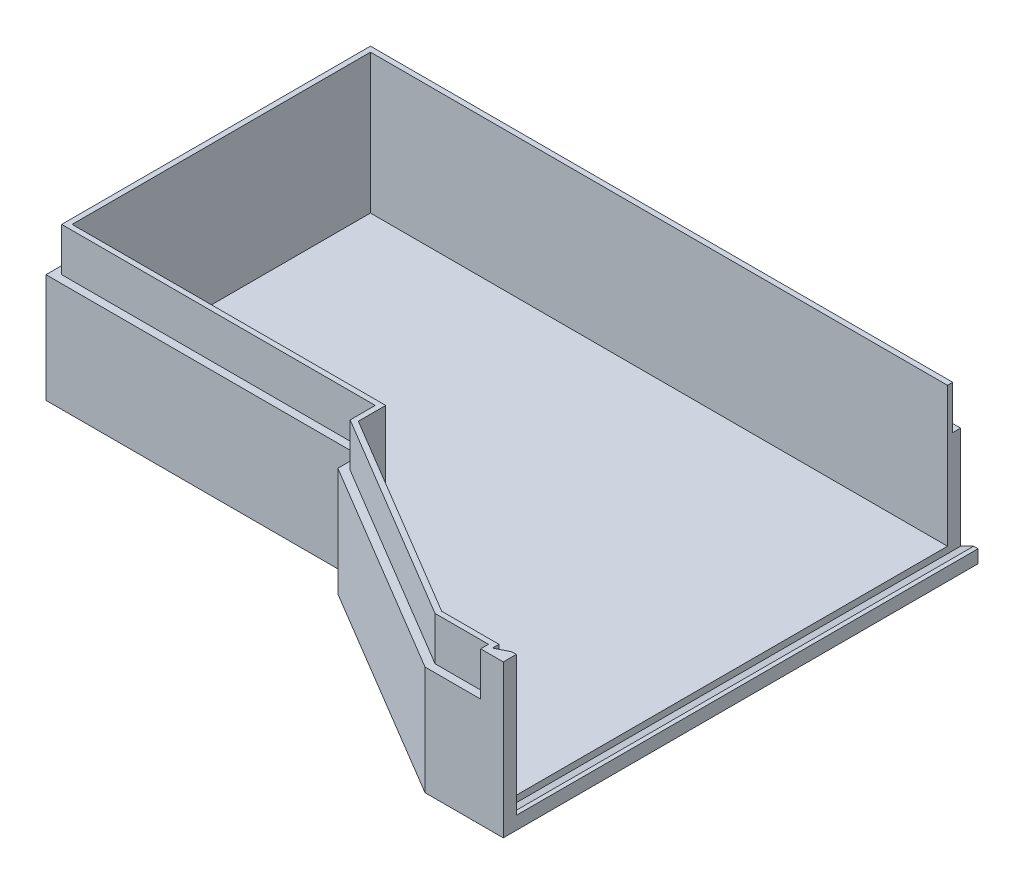
SolidWorks part; units mm, degrees
ref_plane "Front Plane" through (0, 0, 0) normal (0, 0, 1) x (1, 0, 0)
ref_plane "Top Plane" through (0, 0, 0) normal (0, 1, 0) x (1, 0, 0)
ref_plane "Right Plane" through (0, 0, 0) normal (1, 0, 0) x (0, 0, -1)
sketch "PCB" plane through (0, 0, 0) normal (0, 1, 0) x (1, 0, 0)
  line L0 (0, 0) -> (131.5, 0)
  line L1 (131.5, 0) -> (131.5, -102)
  line L2 (131.5, -102) -> (119, -102)
  line L3 (0, 0) -> (0, -67.5)
  line L4 (0, -67.5) -> (72, -67.5)
  line L5 (72, -67.5) -> (72, -74)
  line L6 (72, -74) -> (119, -102)
  line L7 (71.5, -74.2841) -> (118.8624, -102.5)
  line L8 (132, -102.5) -> (118.8624, -102.5)
  line L9 (132, 0.5) -> (132, -102.5)
  line L10 (-0.5, 0.5) -> (132, 0.5)
  line L11 (-0.5, 0.5) -> (-0.5, -68)
  line L12 (-0.5, -68) -> (71.5, -68)
  line L13 (71.5, -68) -> (71.5, -74.2841)
  line L14 (68.5, -75.9889) -> (118.0365, -105.5)
  line L15 (135, -105.5) -> (118.0365, -105.5)
  line L17 (-3.5, 3.5) -> (135, 3.5)
  line L18 (-3.5, 3.5) -> (-3.5, -71)
  line L19 (-3.5, -71) -> (68.5, -71)
  line L20 (68.5, -71) -> (68.5, -75.9889)
  line L22 (135, 3.5) -> (136, 3.5)
  line L24 (135, -105.5) -> (136, -105.5)
  line L25 (136, 3.5) -> (136, -105.5)
  line L26 (135, 3.5) -> (135, -105.5) construction
  dimension "D1" = 131.5
  dimension "D2" = 102
  dimension "D3" = 12.5
  dimension "D4" = 67.5
  dimension "D5" = 72
  dimension "D6" = 6.5
  dimension "D9" = 1
  dimension "D7" = 0.5
  dimension "D8" = 3
extrude "Boss-Extrude1" add sketch "PCB" along normal blind 35 contours L25 L24 L15 L14 L20 L19 L18 L17 L22
sketch "Sketch4" plane through (0, 35, 0) normal (0, 1, 0) x (1, 0, 0)
  line L14 (133, 0.5) -> (-0.5, 0.5)
  line L15 (-0.5, 0.5) -> (-0.5, -68)
  line L16 (-0.5, -68) -> (71.5, -68)
  line L17 (71.5, -68) -> (71.5, -74.2841)
  line L18 (71.5, -74.2841) -> (118.8624, -102.5)
  line L19 (118.8624, -102.5) -> (133, -102.5)
  line L20 (133, -102.5) -> (133, 0.5)
  line L21 (133, 0.5) -> (-0.5, 0.5)
  line L22 (-0.5, 0.5) -> (-0.5, -68)
  line L23 (-0.5, -68) -> (71.5, -68)
  line L24 (71.5, -68) -> (71.5, -74.2841)
  line L25 (71.5, -74.2841) -> (118.8624, -102.5)
  line L26 (118.8624, -102.5) -> (133, -102.5)
  line L27 (133, -102.5) -> (133, 0.5)
  dimension "D1" = 3
extrude "Cut-Extrude1" cut sketch "Sketch4" against normal blind 32
sketch "Sketch5" plane through (0, 35, 0) normal (0, 1, 0) x (1, 0, 0)
  line L0 (118.8624, -102.5) -> (133, -102.5) construction
  line L1 (136, 3.5) -> (132, 3.5)
  line L2 (136, 3.5) -> (136, -102.5)
  line L3 (136, -102.5) -> (132, -102.5)
  line L4 (132, 3.5) -> (132, -102.5)
  dimension "D1" = 4
extrude "Cut-Extrude2" cut sketch "Sketch5" against normal blind 32
sketch "Sketch6" plane through (0, 3, 0) normal (0, 1, 0) x (1, 0, 0)
  line L0 (118.8624, -102.5) -> (136, -102.5) construction
  line L1 (132, 3.5) -> (135, 3.5)
  line L2 (132, 3.5) -> (132, -102.5)
  line L3 (132, -102.5) -> (135, -102.5)
  line L4 (135, 3.5) -> (135, -102.5)
  dimension "D1" = 3
extrude "Cut-Extrude3" cut sketch "Sketch6" against normal blind 1.5
sketch "Sketch7" plane through (0, 0, 102.5) normal (0, 0, -1) x (-1, 0, 0)
  line L0 (-118.8624, 35) -> (-136, 35) construction
  line L1 (-132, 1.5) -> (-135, 1.5)
  line L2 (-132, 1.5) -> (-132, 35)
  line L3 (-132, 35) -> (-135, 35)
  line L4 (-135, 1.5) -> (-135, 35)
  dimension "D1" = 3
extrude "Cut-Extrude4" cut sketch "Sketch7" against normal blind 1.5
sketch "Sketch10" plane through (0, 35, 0) normal (0, 1, 0) x (1, 0, 0)
  line L13 (130.8, -105.5) -> (118.0365, -105.5)
  line L14 (130.8, -103.7) -> (130.8, -105.5)
  line L15 (118.0365, -105.5) -> (136, -105.5) construction
  line L16 (118.0365, -105.5) -> (68.5, -75.9889)
  line L17 (68.5, -75.9889) -> (68.5, -71)
  line L18 (68.5, -71) -> (-3.5, -71)
  line L19 (132, 1.7) -> (-1.7, 1.7)
  line L20 (-1.7, 1.7) -> (-1.7, -69.2)
  line L21 (-1.7, -69.2) -> (70.3, -69.2)
  line L22 (70.3, -69.2) -> (70.3, -74.966)
  line L23 (118.532, -103.7) -> (132, -103.7)
  line L24 (70.3, -74.966) -> (118.532, -103.7)
  line L25 (132, 1.7) -> (-1.7, 1.7)
  line L26 (-1.7, 1.7) -> (-1.7, -69.2)
  line L27 (-1.7, -69.2) -> (70.3, -69.2)
  line L28 (70.3, -69.2) -> (70.3, -74.966)
  line L29 (118.532, -103.7) -> (130.8, -103.7)
  line L30 (70.3, -74.966) -> (118.532, -103.7)
  line L31 (-3.5, -71) -> (-3.5, 3.5)
  line L32 (-3.5, 3.5) -> (132, 3.5)
  line L33 (132, 3.5) -> (132, 1.7)
  dimension "D1" = 1.2
extrude "Cut-Extrude5" cut sketch "Sketch10" against normal blind 10
sketch "Sketch11" plane through (0, 1.5, 0) normal (0, 1, 0) x (1, 0, 0)
  line L0 (132, -104) -> (135, -102.5)
  line L1 (132, -104) -> (135, -104)
  line L4 (135, -104) -> (135, -102.5)
extrude "Boss-Extrude2" add sketch "Sketch11" along normal blind 33.5
sketch "Sketch13" plane through (0, 0, 105.5) normal (0, 0, 1) x (1, 0, 0)
  line L5 (132, 1.5) -> (135, 3)
  line L6 (136, 0) -> (135, 0) construction
  line L11 (136, 0) -> (136, 1.5) construction
  line L12 (136, 1.5) -> (135, 1.5) construction
  line L13 (135, 0) -> (135, 1.5) construction
  line L14 (135, 1.5) -> (132, 1.5)
  line L15 (135, 1.5) -> (135, 3)
  dimension "D1" = 1
  dimension "D2" = 1.5
extrude "Boss-Extrude3" add sketch "Sketch13" against normal blind 109
